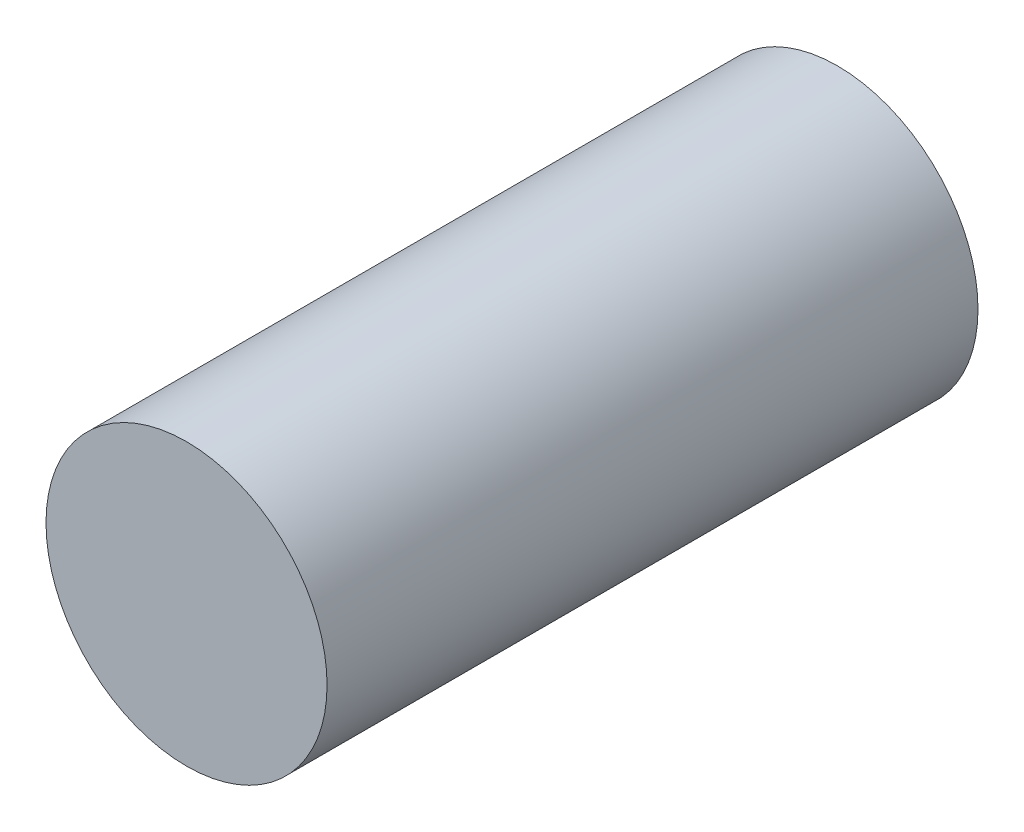
SolidWorks part; units mm, degrees
ref_plane "Plan de face" through (0, 0, 0) normal (0, 0, 1) x (1, 0, 0)
ref_plane "Plan de dessus" through (0, 0, 0) normal (0, 1, 0) x (1, 0, 0)
ref_plane "Plan de droite" through (0, 0, 0) normal (1, 0, 0) x (0, 0, -1)
sketch "Esquisse1" plane through (0, 0, 0) normal (0, 0, 1) x (1, 0, 0)
  circle A0 centre (0, 0) radius 2.5
  dimension "D1" = 5
extrude "Boss.-Extru.1" add sketch "Esquisse1" along normal blind 11.58
